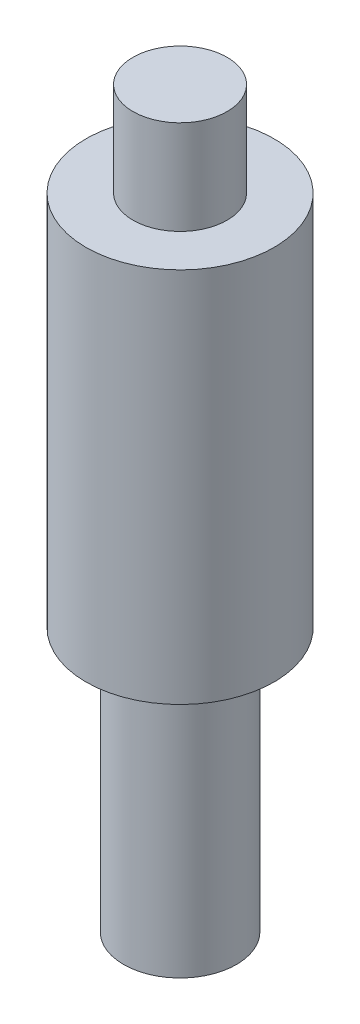
SolidWorks part; units mm, degrees
ref_plane "前视基准面" through (0, 0, 0) normal (0, 0, 1) x (1, 0, 0)
ref_plane "上视基准面" through (0, 0, 0) normal (0, 1, 0) x (1, 0, 0)
ref_plane "右视基准面" through (0, 0, 0) normal (1, 0, 0) x (0, 0, -1)
other "Configuration Table"
sketch "草图1" plane through (0, 0, 0) normal (0, 1, 0) x (1, 0, 0)
  circle A0 centre (0, 0) radius 1.5
  dimension "D1" = 3
extrude "凸台-拉伸1" add sketch "草图1" along normal blind 7 contours A0
sketch "草图2" plane through (0, 7, 0) normal (0, 1, 0) x (1, 0, 0)
  circle A0 centre (0, 0) radius 2.5
  dimension "D1" = 5
extrude "凸台-拉伸2" add sketch "草图2" along normal blind 10 contours A0
sketch "草图3" plane through (0, 17, 0) normal (0, 1, 0) x (1, 0, 0)
  circle A0 centre (0, 0) radius 1.25
  dimension "D1" = 2.5
extrude "凸台-拉伸3" add sketch "草图3" along normal blind 2.5
